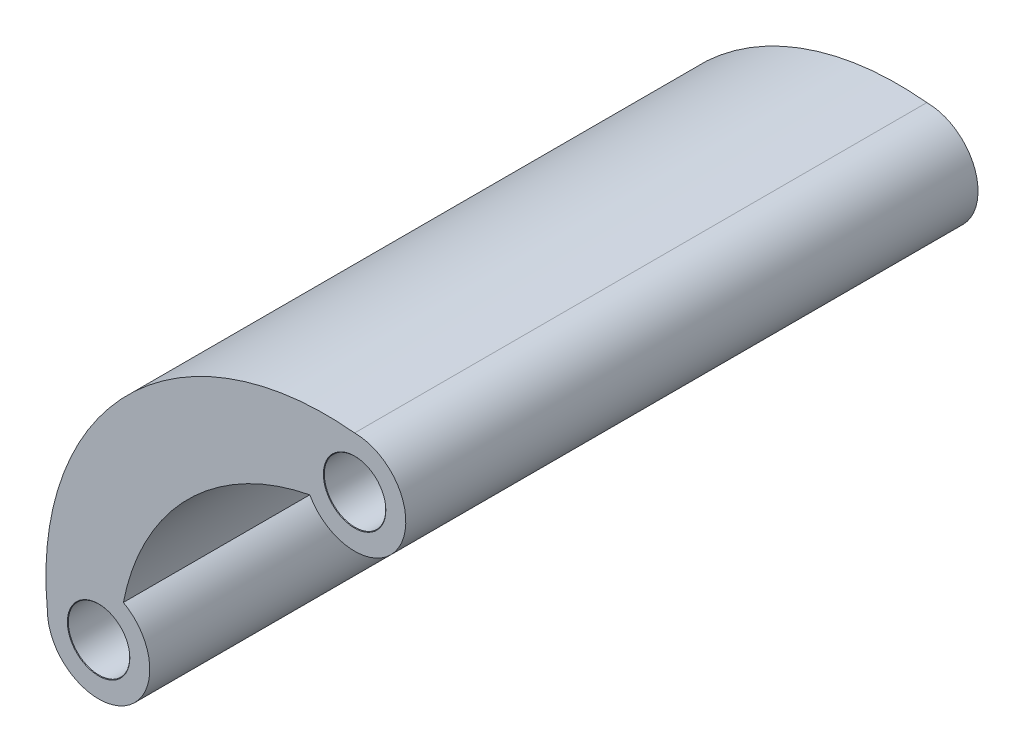
SolidWorks part; units mm, degrees
ref_plane "Front Plane" through (0, 0, 0) normal (1, 0, 0) x (0, 1, 0)
ref_plane "Top Plane" through (0, 0, 0) normal (0, 0, 1) x (0, 1, 0)
ref_plane "Right Plane" through (0, 0, 0) normal (0, 1, 0) x (-1, 0, 0)
sketch "Sketch1" plane through (0, 0, 0) normal (0, 0, 1) x (0, 1, 0)
  line L0 (0, -12.5) -> (0, 12.5) construction
  line L1 (-12.5, 0) -> (12.5, 0) construction
  line L2 (0, 0) -> (1.4142, 1.4142) construction
  line L3 (0, 0) -> (-1.4142, -1.4142) construction
  line L4 (0, 12.5) -> (12.5, 0) construction
  circle A0 centre (0, 12.5) radius 2.5
  circle A3 centre (12.5, 0) radius 2.5
  arc A4 (0, 15) -> (15, 0) centre (1.4142, 1.4142) cw
  arc A5 (2.1877, 11.29) -> (11.29, 2.1877) centre (0, 0) cw
  circle A8 centre (0, 0) radius 13.75 construction
  point P4 (0, 0)
  point P8 (0, 0)
  dimension "D3" = 5
  dimension "D4" = 5
  dimension "D5" = 11.5
  dimension "D6" = 45
  dimension "D8" = 2
  dimension "D9" = 27.5
  dimension "D1" = 25
  dimension "D2" = 25
  dimension "D10" = 2
extrude "Boss-Extrude1" add sketch "Sketch1" along normal blind 27.94
hole_wizard "Ø3.0mm Dowel Hole1" positions "Sketch3" profile "Sketch5" hole size "Ø3.0" standard "ANSI Metric" end condition through all
sketch "Sketch3" plane through (0, 0, 27.94) normal (0, 0, 1) x (1, 0, 0)
  point P0 (0, 12.5)
  point P3 (0, -12.5)
  point P6 (-12.5, 0)
sketch "Sketch5" plane through (0, 12.5, 27.94) normal (1, 0, 0) x (0, -1, 0)
  line L0 (0, 0) -> (0, 27.94)
  line L1 (0, 27.94) -> (1.5, 27.94)
  line L2 (1.5, 27.94) -> (1.5, 0.021)
  line L3 (1.5, 0.021) -> (1.525, 0)
  line L5 (1.525, 0) -> (0, 0)
  line L6 (-1.5, 0.021) -> (-1.525, 0) construction
  line L11 (0, -6.35) -> (0, 107.95) construction
  dimension "Thru Hole Dia." = 3
  dimension "Thru Hole Depth" = 27.94
  dimension "Near C'Sink Dia." = 3.05
  dimension "Near C'Sink Angle" = 100
equation "\"Alum Bracket Thickness\"= 0.225in"
equation "\"D1@Boss-Extrude1\"=1.1in"
equation "\"spur gear gap\"= 0.194in"
